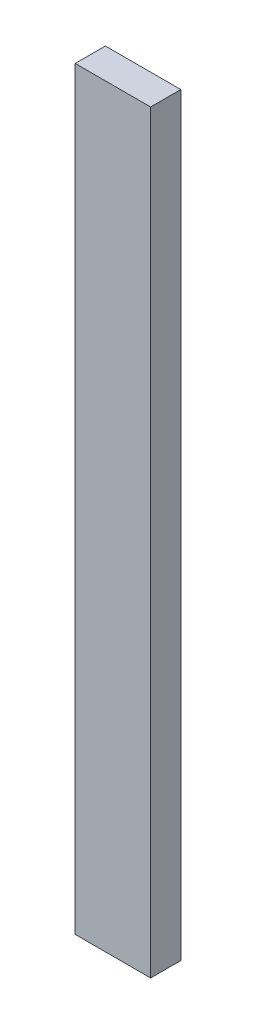
SolidWorks part; units mm, degrees
ref_plane "Front Plane" through (0, 0, 0) normal (0, 0, 1) x (1, 0, 0)
ref_plane "Top Plane" through (0, 0, 0) normal (0, 1, 0) x (1, 0, 0)
ref_plane "Right Plane" through (0, 0, 0) normal (1, 0, 0) x (0, 0, -1)
sketch "Sketch1" plane through (0, 0, 0) normal (0, 0, 1) x (1, 0, 0)
  line L1 (-2.5, 25) -> (2.5, 25)
  line L2 (-2.5, 25) -> (-2.5, -25)
  line L3 (-2.5, -25) -> (2.5, -25)
  line L4 (2.5, 25) -> (2.5, -25)
  line L5 (-2.5, 25) -> (2.5, -25) construction
  line L6 (-2.5, -25) -> (2.5, 25) construction
  point P0 (0, 0)
  dimension "D1" = 5
  dimension "D2" = 50
extrude "Boss-Extrude1" add sketch "Sketch1" along normal blind 2
